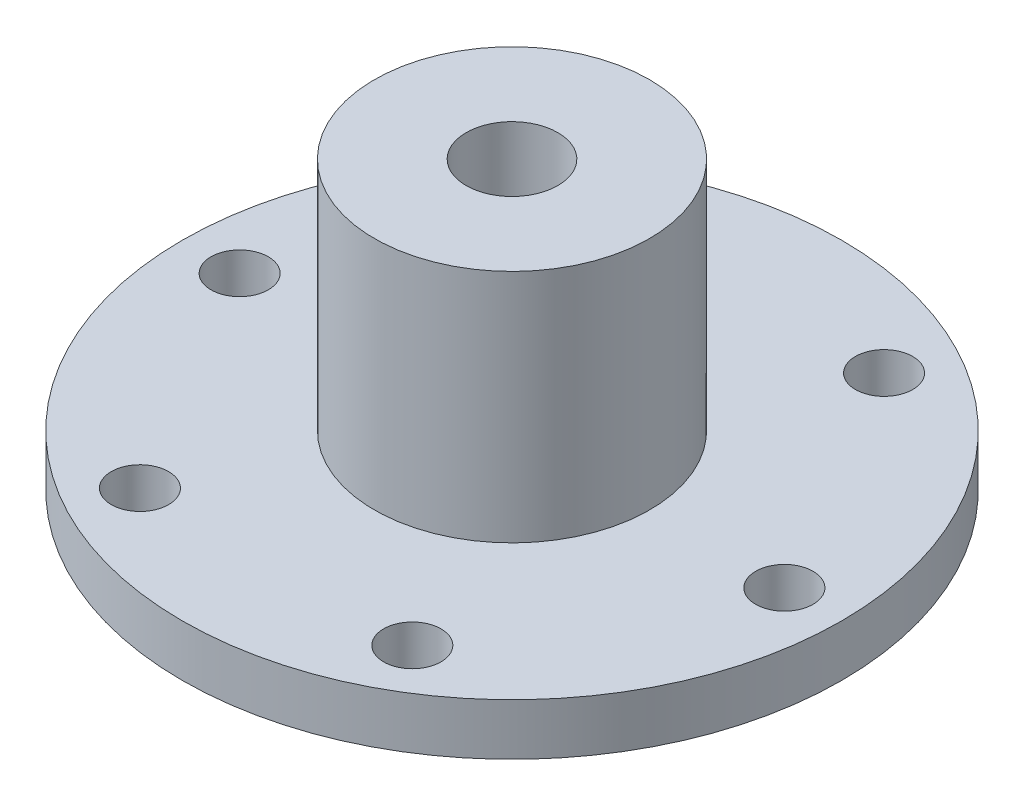
SolidWorks part; units mm, degrees
ref_plane "Plan de face" through (0, 0, 0) normal (0, 0, 1) x (1, 0, 0)
ref_plane "Plan de dessus" through (0, 0, 0) normal (0, 1, 0) x (1, 0, 0)
ref_plane "Plan de droite" through (0, 0, 0) normal (1, 0, 0) x (0, 0, -1)
sketch "Esquisse1" plane through (0, 0, 0) normal (0, 0, 1) x (1, 0, 0)
  line L0 (0, 0) -> (0, 25) construction
  line L1 (4, 0) -> (28.75, 0)
  line L2 (28.75, 0) -> (28.75, 4.5)
  line L3 (28.75, 4.5) -> (12, 4.5)
  line L4 (12, 4.5) -> (12, 25)
  line L5 (12, 25) -> (4, 25)
  line L6 (4, 25) -> (4, 0)
  dimension "D1" = 4
  dimension "D2" = 12
  dimension "D3" = 20.5
  dimension "D4" = 25
  dimension "D5" = 28.75
revolve "Révolution1" add sketch "Esquisse1" angle 360 about L0
sketch "Esquisse2" plane through (0, 0, 0) normal (0, -1, 0) x (1, 0, 0)
  line L0 (0, 0) -> (28.75, 0) construction
  circle A0 centre (0, 0) radius 28.75 construction
  circle A1 centre (23.75, 0) radius 2.5
  circle A2 centre (11.875, -20.5681) radius 2.5
  circle A3 centre (-11.875, -20.5681) radius 2.5
  circle A4 centre (-23.75, 0) radius 2.5
  circle A5 centre (-11.875, 20.5681) radius 2.5
  circle A6 centre (11.875, 20.5681) radius 2.5
  point P15 (0, 0)
  dimension "D1" = 5
  dimension "D2" = 23.75
  dimension "D3" = 6
extrude "Enlèv. mat.-Extru.1" cut sketch "Esquisse2" against normal through all
